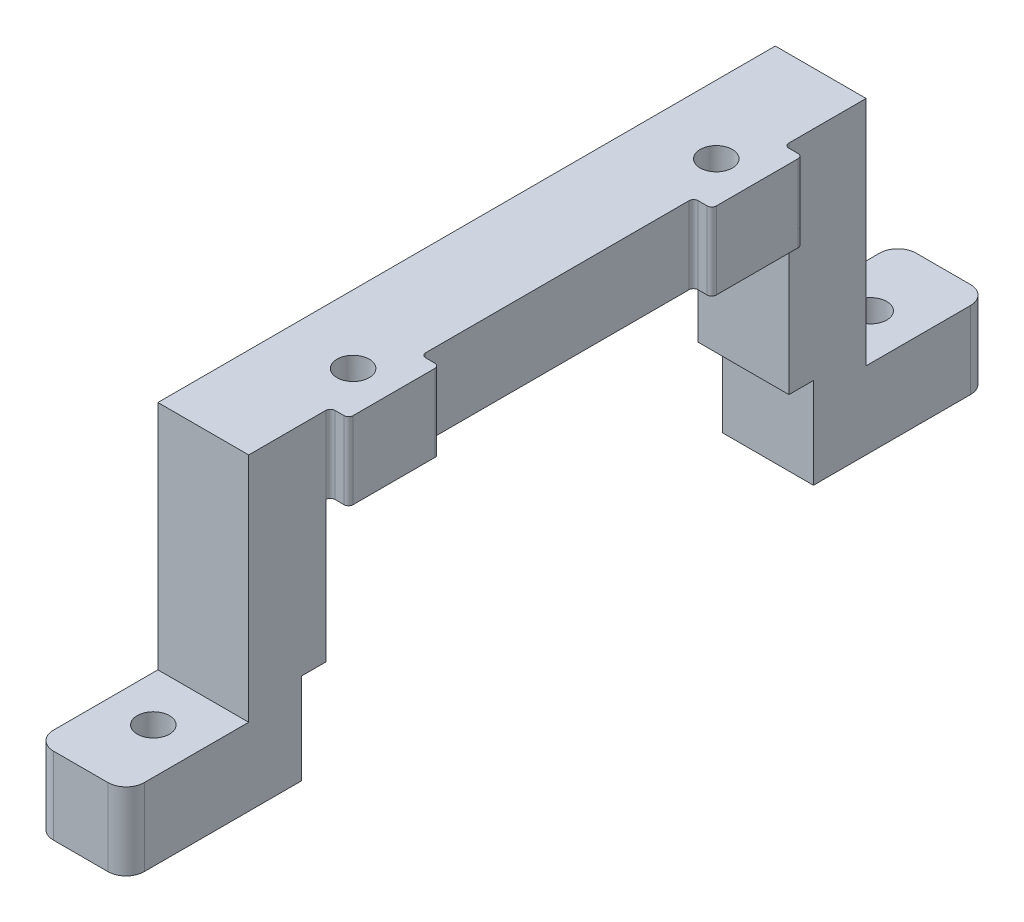
SolidWorks part; units mm, degrees
ref_plane "Front Plane" through (0, 0, 0) normal (0, 0, 1) x (1, 0, 0)
ref_plane "Top Plane" through (0, 0, 0) normal (0, 1, 0) x (1, 0, 0)
ref_plane "Right Plane" through (0, 0, 0) normal (1, 0, 0) x (0, 0, -1)
sketch "Sketch1" plane through (0, 0, 0) normal (1, 0, 0) x (0, 0, -1)
  line L0 (-108.186, 9.2491) -> (-86.186, 9.2491)
  line L1 (-86.186, 9.2491) -> (-86.186, 34.7491)
  line L2 (-86.186, 34.7491) -> (-35.186, 34.7491)
  line L3 (-35.186, 34.7491) -> (-35.186, 9.2491)
  line L4 (-35.186, 9.2491) -> (-13.186, 9.2491)
  line L5 (-26.686, 17.7491) -> (-26.686, 43.2491)
  line L6 (-26.686, 43.2491) -> (-94.686, 43.2491)
  line L7 (-94.686, 43.2491) -> (-94.686, 17.7491)
  line L8 (-94.686, 17.7491) -> (-108.186, 17.7491)
  line L9 (-108.186, 17.7491) -> (-108.186, 9.2491)
  line L10 (-94.686, 17.7491) -> (-86.186, 17.7491) construction
  line L11 (-86.186, 34.7491) -> (-86.186, 43.2491) construction
  line L12 (-13.186, 9.2491) -> (-13.186, 17.7491)
  line L13 (-13.186, 17.7491) -> (-26.686, 17.7491)
  line L14 (-35.186, 17.7491) -> (-26.686, 17.7491) construction
  dimension "D1" = 8.5
  dimension "D2" = 22
  dimension "D3" = 95
  dimension "D4" = 34
extrude "Boss-Extrude1" add sketch "Sketch1" along normal blind 10
sketch "Sketch2" plane through (0, 17.7491, 0) normal (0, 1, 0) x (1, 0, 0)
  line L0 (5, -100.186) -> (5, -108.186) construction
  line L1 (10, -108.186) -> (0, -108.186) construction
  line L6 (5, -21.186) -> (5, -13.186) construction
  line L7 (10, -13.186) -> (0, -13.186) construction
  circle A0 centre (5, -100.186) radius 1.775
  circle A1 centre (5, -21.186) radius 1.775
  dimension "D2" = 3.55
  dimension "D1" = 79
extrude "Cut-Extrude1" cut sketch "Sketch2" against normal through all
sketch "Sketch3" plane through (10, 0, 0) normal (1, 0, 0) x (0, 0, -1)
  line L0 (-26.686, 43.2491) -> (-94.686, 43.2491) construction
  line L1 (-85.686, 43.2491) -> (-75.686, 43.2491)
  line L2 (-85.686, 43.2491) -> (-85.686, 34.7491)
  line L3 (-85.686, 34.7491) -> (-75.686, 34.7491)
  line L4 (-75.686, 43.2491) -> (-75.686, 34.7491)
  line L5 (-86.186, 34.7491) -> (-35.186, 34.7491) construction
  line L6 (-80.686, 34.7491) -> (-80.686, 43.2491) construction
  line L7 (-45.686, 43.2491) -> (-35.686, 43.2491)
  line L8 (-45.686, 43.2491) -> (-45.686, 34.7491)
  line L9 (-45.686, 34.7491) -> (-35.686, 34.7491)
  line L10 (-35.686, 43.2491) -> (-35.686, 34.7491)
  line L11 (-40.686, 34.7491) -> (-40.686, 43.2491) construction
  line L12 (-94.686, 43.2491) -> (-85.686, 43.2491) construction
  line L13 (-35.686, 43.2491) -> (-26.686, 43.2491) construction
  dimension "D1" = 40
  dimension "D2" = 10
extrude "Boss-Extrude2" add sketch "Sketch3" along normal blind 2
sketch "Sketch4" plane through (0, 43.2491, 0) normal (0, 1, 0) x (1, 0, 0)
  line L0 (7.5, -85.686) -> (7.5, -80.686) construction
  line L1 (12, -85.686) -> (10, -85.686) construction
  line L2 (7.5, -80.686) -> (7.5, -75.686) construction
  line L3 (7.5, -40.686) -> (7.5, -35.686) construction
  line L4 (12, -35.686) -> (10, -35.686) construction
  line L5 (12, -75.686) -> (10, -75.686) construction
  line L6 (7.5, -45.686) -> (7.5, -40.686) construction
  line L7 (12, -45.686) -> (10, -45.686) construction
  circle A0 centre (7.5, -80.686) radius 1.775
  circle A1 centre (7.5, -40.686) radius 1.775
  circle A2 centre (5, -100.186) radius 1.775 construction
  dimension "D1" = 2.5
  dimension "D2" = 3.55
extrude "Cut-Extrude2" cut sketch "Sketch4" against normal through all
fillet "Fillet2" radius 0.5 8 edges at (10, 38.9991, 35.686) (10, 38.9991, 45.686) (12, 38.9991, 35.686) (12, 38.9991, 45.686) (12, 38.9991, 75.686) (12, 38.9991, 85.686)
fillet "Fillet3" radius 2 4 edges at (0, 13.4991, 13.186) (10, 13.4991, 13.186) (10, 13.4991, 108.186) (0, 13.4991, 108.186)
sketch "Sketch5" plane through (0, 9.2491, 0) normal (0, -1, 0) x (1, 0, 0)
  line L0 (0, 106.186) -> (0, 86.186) construction
  line L1 (0, 88.886) -> (10, 88.886)
  line L2 (0, 88.886) -> (0, 32.486)
  line L3 (0, 32.486) -> (10, 32.486)
  line L4 (10, 88.886) -> (10, 32.486)
  line L5 (10, 35.186) -> (10, 15.186) construction
  line L6 (5, 86.186) -> (5, 88.886) construction
  line L7 (10, 86.186) -> (0, 86.186) construction
  line L8 (5, 32.486) -> (5, 35.186) construction
  line L9 (10, 35.186) -> (0, 35.186) construction
  dimension "D1" = 56.4
extrude "Cut-Extrude3" cut sketch "Sketch5" against normal blind 10
sketch "Sketch6" plane through (0, 34.7491, 0) normal (0, -1, 0) x (1, 0, 0)
  circle A0 centre (7.5, 80.686) radius 3.25
  circle A1 centre (7.5, 40.686) radius 3.25
  circle A2 centre (7.5, 80.686) radius 1.775 construction
  circle A3 centre (7.5, 40.686) radius 1.775 construction
  dimension "D1" = 6.5
extrude "Cut-Extrude4" cut sketch "Sketch6" against normal blind 5
